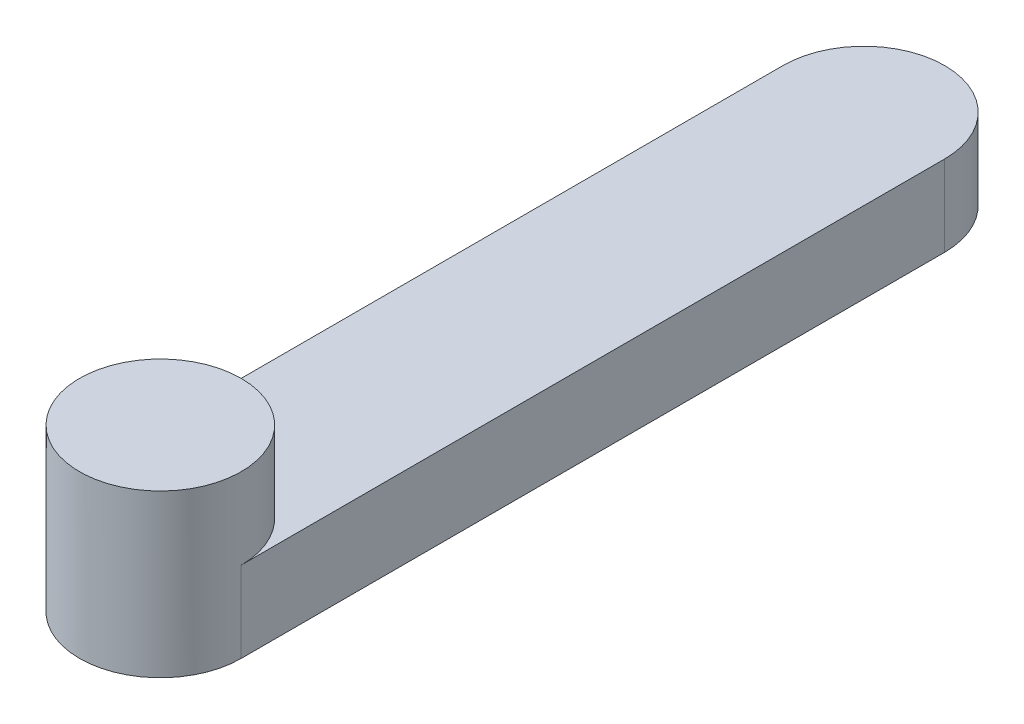
SolidWorks part; units mm, degrees
ref_plane "Front Plane" through (0, 0, 0) normal (0, 0, 1) x (1, 0, 0)
ref_plane "Top Plane" through (0, 0, 0) normal (0, 1, 0) x (1, 0, 0)
ref_plane "Right Plane" through (0, 0, 0) normal (1, 0, 0) x (0, 0, -1)
sketch "Sketch1" plane through (0, 0, 0) normal (0, 1, 0) x (1, 0, 0)
  line L0 (0, 0) -> (0, -22.098) construction
  line L1 (2.54, 0) -> (2.54, -22.098)
  line L2 (-2.54, 0) -> (-2.54, -22.098)
  arc A0 (2.54, 0) -> (-2.54, 0) centre (0, 0) ccw
  arc A1 (-2.54, -22.098) -> (2.54, -22.098) centre (0, -22.098) ccw
  point P3 (0, -11.049)
  dimension "D2" = 5.08
  dimension "D3" = 22.098
extrude "Boss-Extrude1" add sketch "Sketch1" along normal blind 2.54
sketch "Sketch2" plane through (0, 2.54, 0) normal (0, 1, 0) x (1, 0, 0)
  arc A0 (-2.54, -22.098) -> (2.54, -22.098) centre (0, -22.098) ccw construction
  arc A1 (-2.54, -22.098) -> (2.54, -22.098) centre (0, -22.098) ccw
  arc A2 (-2.54, -22.098) -> (2.54, -22.098) centre (0, -22.098) cw
extrude "Boss-Extrude2" add sketch "Sketch2" along normal blind 2.54
